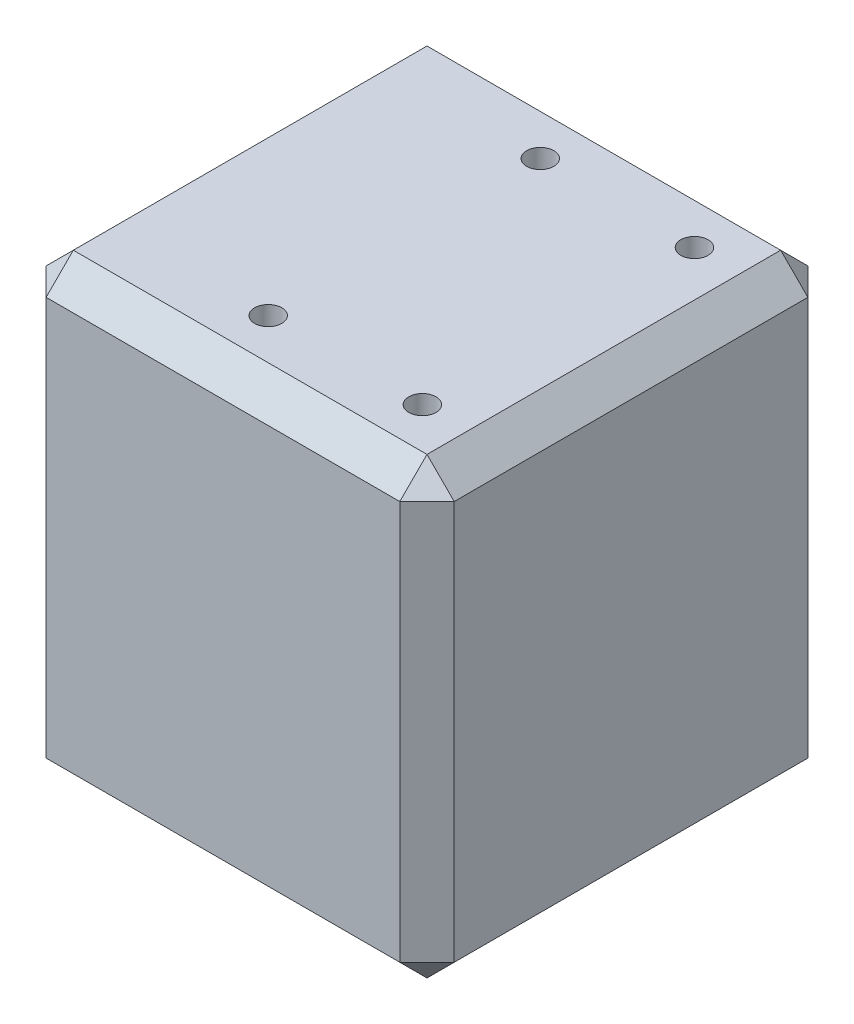
SolidWorks part; units mm, degrees
ref_plane "前视基准面" through (0, 0, 0) normal (0, 0, 1) x (1, 0, 0)
ref_plane "上视基准面" through (0, 0, 0) normal (0, 1, 0) x (1, 0, 0)
ref_plane "右视基准面" through (0, 0, 0) normal (1, 0, 0) x (0, 0, -1)
sketch "Sketch1" plane through (0, 0, 0) normal (0, 1, 0) x (1, 0, 0)
  line L1 (-22.5, 22.5) -> (22.5, 22.5)
  line L2 (-22.5, 22.5) -> (-22.5, -22.5)
  line L3 (-22.5, -22.5) -> (22.5, -22.5)
  line L4 (22.5, 22.5) -> (22.5, -22.5)
  line L5 (-22.5, 22.5) -> (22.5, -22.5) construction
  line L6 (-22.5, -22.5) -> (22.5, 22.5) construction
  point P0 (0, 0)
  dimension "D1" = 45
  dimension "D2" = 45
extrude "Boss-Extrude1" add sketch "Sketch1" along normal blind 50
sketch "Sketch2" plane through (0, 0, -22.5) normal (0, 0, -1) x (-1, 0, 0)
  circle A0 centre (0, 12.5) radius 4.15
  dimension "D1" = 8.3
  dimension "D2" = 12.5
extrude "Cut-Extrude1" cut sketch "Sketch2" against normal blind 30
sketch "Sketch3" plane through (-22.5, 0, 0) normal (-1, 0, 0) x (0, 0, 1)
  line L1 (-22.5, 50) -> (22.5, 50) construction
  circle A0 centre (0, 37.5) radius 4.15
  dimension "D1" = 8.3
  dimension "D2" = 12.5
extrude "Cut-Extrude2" cut sketch "Sketch3" against normal blind 30
chamfer "Chamfer1" distance 3 angle 45 12 edges at (0, 50, 22.5) (-22.5, 50, 0) (0, 50, -22.5) (22.5, 50, 0) (0, 0, 22.5) (22.5, 25, 22.5) (22.5, 0, 0) (-22.5, 25, 22.5) (-22.5, 0, 0) (-22.5, 25, -22.5) (0, 0, -22.5) (22.5, 25, -22.5)
sketch "Sketch5" plane through (0, 50, 0) normal (0, 1, 0) x (1, 0, 0)
  line L0 (19.5, 0) -> (0, 0) construction
  line L1 (22.5, 19.5) -> (22.5, -19.5) construction
  line L2 (19.5, -19.5) -> (19.5, 19.5) construction
  circle A0 centre (-2.51, -15) radius 1.5
  circle A1 centre (14.49, -15) radius 1.5
  circle A2 centre (14.49, 15) radius 1.5
  circle A3 centre (-2.51, 15) radius 1.5
  point P13 (0, 0)
  point P14 (0, 0)
  point P15 (0, 0)
  point P16 (0, 0)
  point P17 (19.5, 0)
  dimension "D1" = 8.01
  dimension "D2" = 17
  dimension "D3" = 15
  dimension "D4" = 3
  dimension "D5" = 3
extrude "Cut-Extrude3" cut sketch "Sketch5" against normal blind 10
